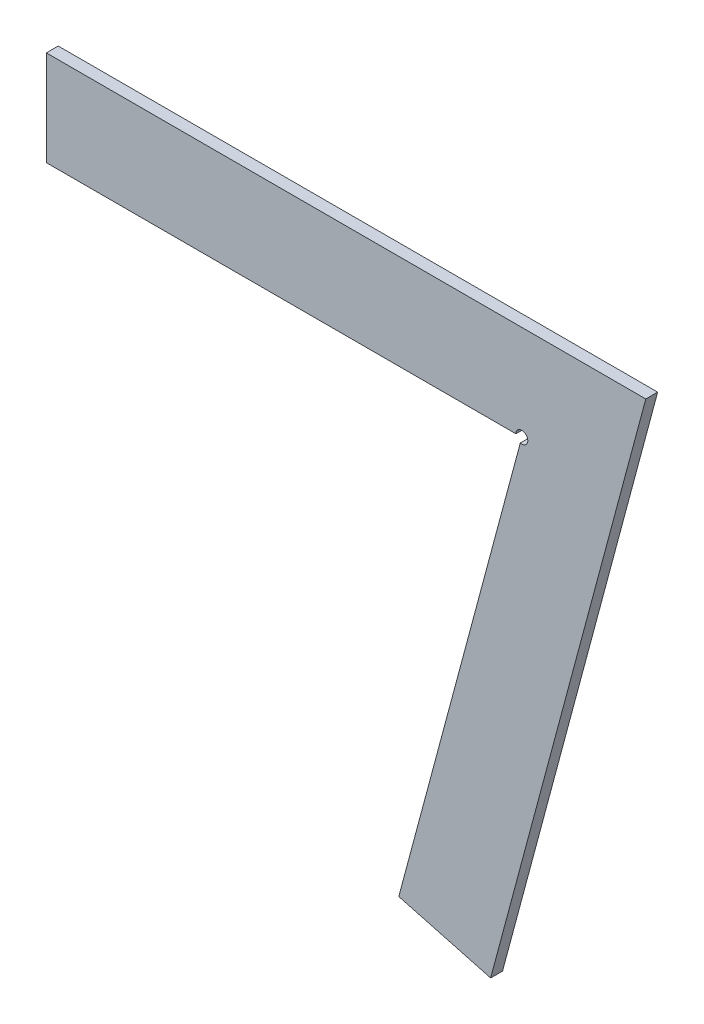
SolidWorks part; units mm, degrees
ref_plane "Plan de face" through (0, 0, 0) normal (0, 0, 1) x (1, 0, 0)
ref_plane "Plan de dessus" through (0, 0, 0) normal (0, 1, 0) x (1, 0, 0)
ref_plane "Plan de droite" through (0, 0, 0) normal (1, 0, 0) x (0, 0, -1)
sketch "Esquisse1" plane through (0, 0, 0) normal (0, 0, 1) x (1, 0, 0)
  line L0 (0, 0) -> (0, -40)
  line L1 (0, -40) -> (200, -40)
  line L2 (200, -40) -> (148.2362, -233.1852)
  line L3 (148.2362, -233.1852) -> (186.8732, -243.5379)
  line L4 (186.8732, -243.5379) -> (252.129, 0)
  line L5 (252.129, 0) -> (0, 0)
  point P3 (71.8505, -252.0742)
  point P8 (100, -40)
  dimension "D1" = 75
  dimension "D2" = 40
  dimension "D3" = 40
  dimension "D4" = 200
  dimension "D5" = 200
extrude "Boss.-Extru.1" add sketch "Esquisse1" along normal blind 5
sketch "Esquisse2" plane through (0, 0, 5) normal (0, 0, 1) x (1, 0, 0)
  circle A0 centre (200, -40) radius 2.5
  dimension "D1" = 5
extrude "Enlèv. mat.-Extru.1" cut sketch "Esquisse2" against normal through all
